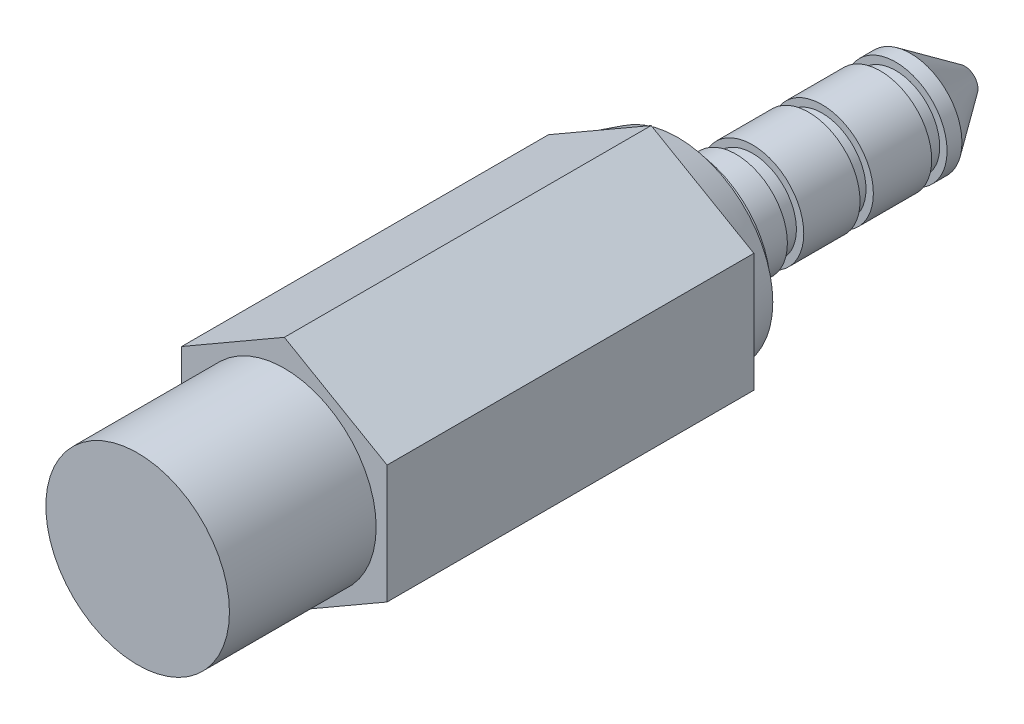
SolidWorks part; units mm, degrees
material "Acero al carbono no aleado"
ref_plane "Alzado" through (0, 0, 0) normal (0, 0, 1) x (1, 0, 0)
ref_plane "Planta" through (0, 0, 0) normal (0, 1, 0) x (1, 0, 0)
ref_plane "Vista lateral" through (0, 0, 0) normal (1, 0, 0) x (0, 0, -1)
sketch "Croquis1" plane through (0, 0, 0) normal (0, 0, 1) x (1, 0, 0)
  line L1 (0, -8.0829) -> (7, -4.0415)
  line L2 (7, -4.0415) -> (7, 4.0415)
  line L3 (7, 4.0415) -> (0, 8.0829)
  line L4 (0, 8.0829) -> (-7, 4.0415)
  line L5 (-7, 4.0415) -> (-7, -4.0415)
  line L6 (-7, -4.0415) -> (0, -8.0829)
  circle A0 centre (0, 0) radius 7 construction
  dimension "D1" = 14
extrude "Saliente-Extruir1" add sketch "Croquis1" along normal blind 25
sketch "Croquis2" plane through (0, 0, 25) normal (0, 0, 1) x (1, 0, 0)
  circle A0 centre (0, 0) radius 6.2576
extrude "Saliente-Extruir2" add sketch "Croquis2" along normal blind 10
sketch "Croquis3" plane through (0, 0, 0) normal (0, 1, 0) x (1, 0, 0)
  line L0 (0, 21.3821) -> (0.8945, 21.3821)
  line L1 (0.8945, 21.3821) -> (3.5, 17.6825)
  line L2 (3.5, 17.6825) -> (3.5, 16.6668)
  line L3 (3.5, 16.6668) -> (3, 16.6668)
  line L4 (3, 16.6668) -> (3, 15.6205)
  line L5 (3, 15.6205) -> (3.5, 15.6205)
  line L6 (3.5, 15.6205) -> (3.5, 11.6443)
  line L7 (3.5, 11.6443) -> (3, 11.6443)
  line L8 (3, 11.6443) -> (3, 10.7374)
  line L9 (3, 10.7374) -> (3.5, 10.7374)
  line L10 (3.5, 10.7374) -> (3.5, 6.9007)
  line L11 (3.5, 6.9007) -> (3, 6.9007)
  line L12 (3, 6.9007) -> (3, 5.7846)
  line L13 (3, 5.7846) -> (3.5, 5.7846)
  line L14 (3.5, 5.7846) -> (3.5, 2.6455)
  line L15 (3.5, 2.6455) -> (5.4674, 2.6455)
  line L16 (5.4674, 2.6455) -> (5.4674, 1.8084)
  line L17 (5.4674, 1.8084) -> (6.4831, 1.8084)
  line L18 (6.4831, 1.8084) -> (7, 0)
  line L19 (7, 0) -> (0, 0)
  line L20 (0, 0) -> (0, 21.3821)
  dimension "D1" = 3.5
  dimension "D2" = 3
revolve "Revolución1" add sketch "Croquis3" angle 360 about L20
